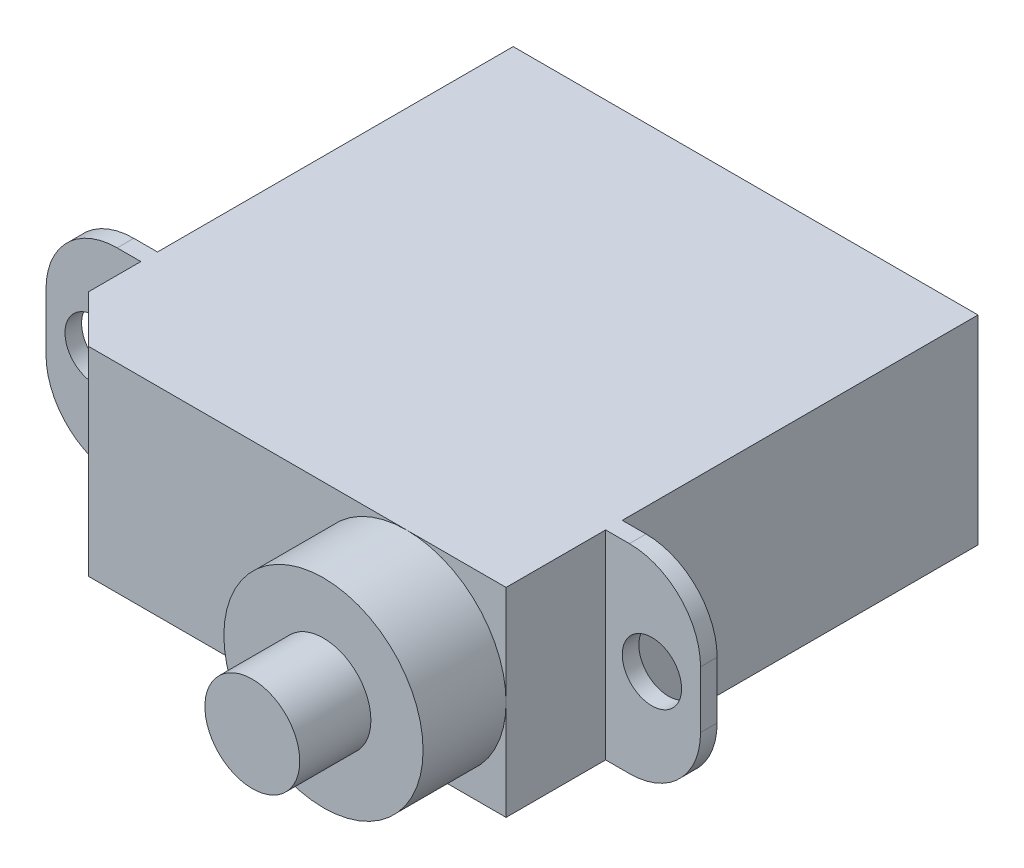
SolidWorks part; units mm, degrees
ref_plane "前基準面" through (0, 0, 0) normal (0, 0, 1) x (1, 0, 0)
ref_plane "上基準面" through (0, 0, 0) normal (0, 1, 0) x (1, 0, 0)
ref_plane "右基準面" through (0, 0, 0) normal (1, 0, 0) x (0, 0, -1)
sketch "草圖1" plane through (0, 0, 0) normal (0, 0, 1) x (1, 0, 0)
  line L1 (-9.8, 4.2) -> (9.8, 4.2)
  line L2 (-9.8, 4.2) -> (-9.8, -4.2)
  line L3 (-9.8, -4.2) -> (9.8, -4.2)
  line L4 (9.8, 4.2) -> (9.8, -4.2)
  line L5 (-9.8, 4.2) -> (9.8, -4.2) construction
  line L6 (-9.8, -4.2) -> (9.8, 4.2) construction
  point P0 (0, 0)
  dimension "D1" = 19.6
  dimension "D2" = 8.4
extrude "填料-伸長1" add sketch "草圖1" along normal blind 19.9
chamfer "導角1" distance 2 angle 45 1 edges at (-9.8, 0, 19.9)
sketch "草圖2" plane through (0, -4.2, 0) normal (0, -1, 0) x (1, 0, 0)
  line L0 (-9.8, 0) -> (9.8, 0) construction
  line L1 (-13.8, 15.7) -> (13.8, 15.7)
  line L2 (-13.8, 15.7) -> (-13.8, 15)
  line L3 (-13.8, 15) -> (13.8, 15)
  line L4 (13.8, 15.7) -> (13.8, 15)
  line L5 (-13.8, 15.7) -> (13.8, 15) construction
  line L6 (-13.8, 15) -> (13.8, 15.7) construction
  point P0 (0, 15.35)
  dimension "D1" = 27.6
  dimension "D2" = 0.7
  dimension "D3" = 15
extrude "填料-伸長2" add sketch "草圖2" against normal up to surface (8.4 mm away) up to face at (-1.56, 4.2, 11.54)
fillet "圓角1" radius 3 4 edges at (13.8, 4.2, 15.35) (13.8, -4.2, 15.35) (-13.8, 4.2, 15.35) (-13.8, -4.2, 15.35)
sketch "草圖3" plane through (0, 0, 15.7) normal (0, 0, 1) x (1, 0, 0)
  circle A0 centre (-11.75, 0) radius 1.25
  circle A1 centre (11.75, 0) radius 1.25
  dimension "D3" = 2.5
  dimension "D4" = 2.5
  dimension "D1" = 23.5
  dimension "D2" = 11.75
extrude "除料-伸長1" cut sketch "草圖3" against normal up to next
sketch "草圖4" plane through (0, 0, 19.9) normal (0, 0, 1) x (1, 0, 0)
  line L0 (9.8, -4.2) -> (9.8, 4.2) construction
  circle A0 centre (5.6, 0) radius 4.2
  dimension "D1" = 8.4
extrude "填料-伸長3" add sketch "草圖4" along normal blind 3.5
sketch "草圖5" plane through (0, 0, 23.4) normal (0, 0, 1) x (1, 0, 0)
  circle A0 centre (5.6, 0) radius 2
  dimension "D1" = 4
extrude "填料-伸長4" add sketch "草圖5" along normal blind 3
